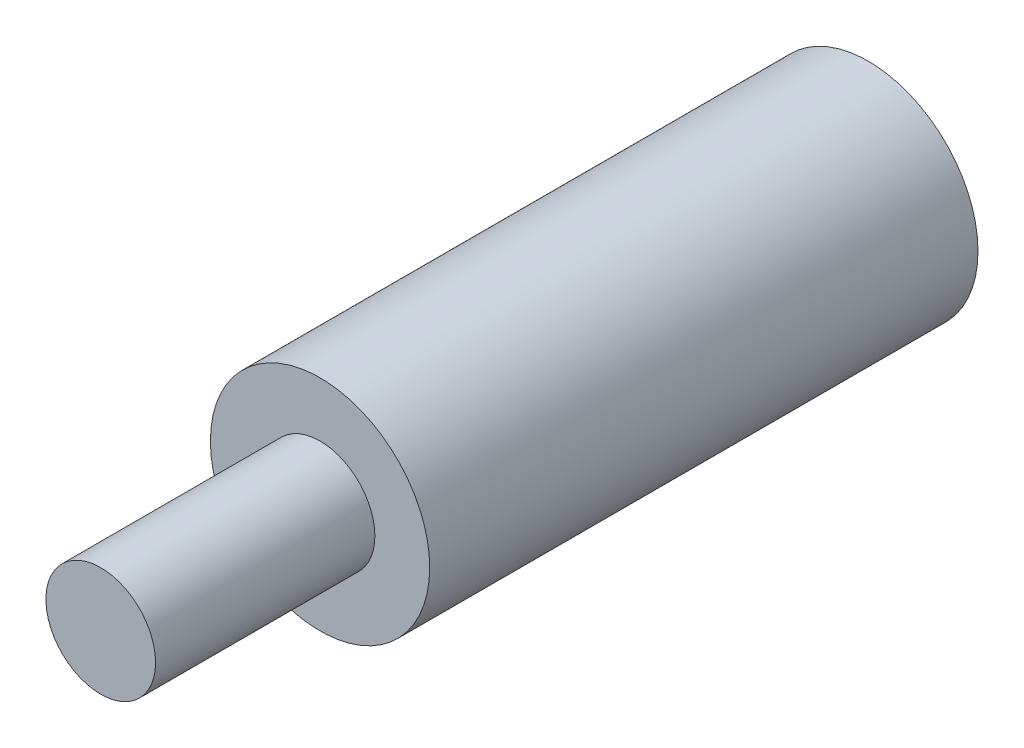
SolidWorks part; units mm, degrees
material "铍红铜, UNS C17200"
ref_plane "前视基准面" through (0, 0, 0) normal (0, 0, 1) x (1, 0, 0)
ref_plane "上视基准面" through (0, 0, 0) normal (0, 1, 0) x (1, 0, 0)
ref_plane "右视基准面" through (0, 0, 0) normal (1, 0, 0) x (0, 0, -1)
sketch "草图1" plane through (0, 0, 0) normal (0, 0, 1) x (1, 0, 0)
  circle A0 centre (0, 0) radius 1.5
  circle A1 centre (0, 0) radius 3
  dimension "D1" = 6
  dimension "D2" = 3
extrude "凸台-拉伸1" add sketch "草图1" along normal blind 15
sketch "草图2" plane through (0, 0, 15) normal (0, 0, 1) x (1, 0, 0)
  circle A0 centre (0, 0) radius 1.5 construction
  circle A1 centre (0, 0) radius 1.5
extrude "凸台-拉伸2" add sketch "草图2" along normal blind 6 separate body
